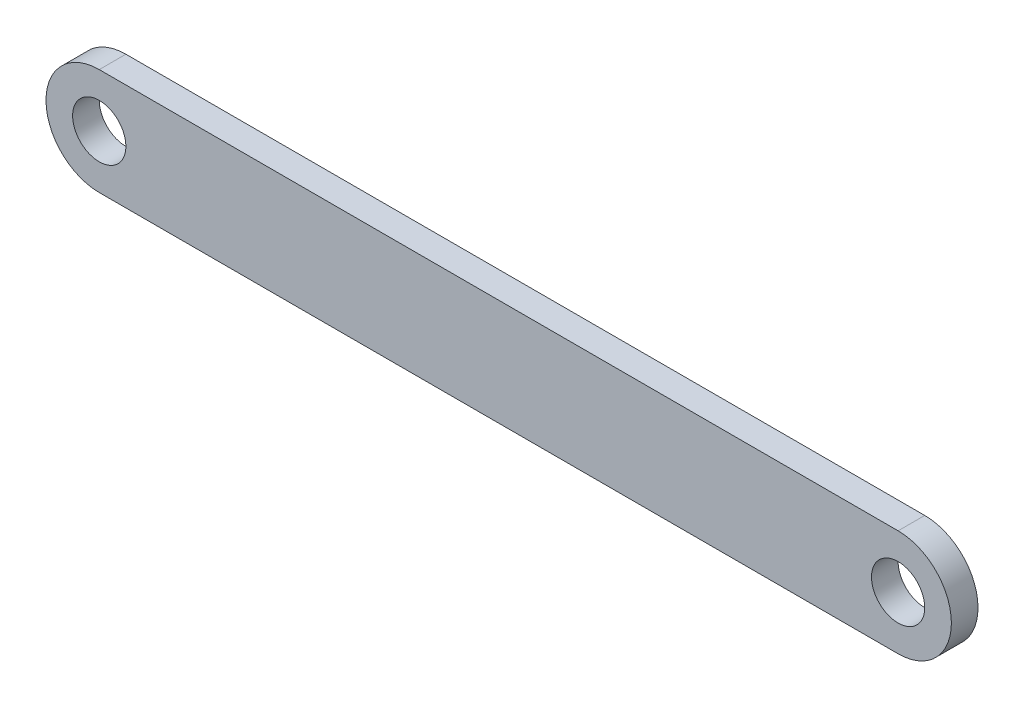
SolidWorks part; units mm, degrees
ref_plane "Ön Düzlem" through (0, 0, 0) normal (0, 0, 1) x (1, 0, 0)
ref_plane "Üst Düzlem" through (0, 0, 0) normal (0, 1, 0) x (1, 0, 0)
ref_plane "Sağ Düzlem" through (0, 0, 0) normal (1, 0, 0) x (0, 0, -1)
sketch "Çizim3" plane through (0, 0, 0) normal (0, 0, 1) x (1, 0, 0)
  line L0 (-102.8846, 19.2308) -> (47.1154, 19.2308) construction
  line L1 (-102.8846, 29.2308) -> (47.1154, 29.2308)
  line L2 (-102.8846, 9.2308) -> (47.1154, 9.2308)
  arc A0 (-102.8846, 29.2308) -> (-102.8846, 9.2308) centre (-102.8846, 19.2308) ccw
  arc A1 (47.1154, 9.2308) -> (47.1154, 29.2308) centre (47.1154, 19.2308) ccw
  circle A2 centre (-102.8846, 19.2308) radius 5
  circle A3 centre (47.1154, 19.2308) radius 5
  point P2 (-27.8846, 19.2308)
  dimension "D1" = 150
  dimension "D2" = 20
extrude "Yükseklik-Ekstrüzyon1" add sketch "Çizim3" along normal blind 5
sketch "Çizim4" plane through (0, 0, 0) normal (0, 0, 1) x (1, 0, 0)
